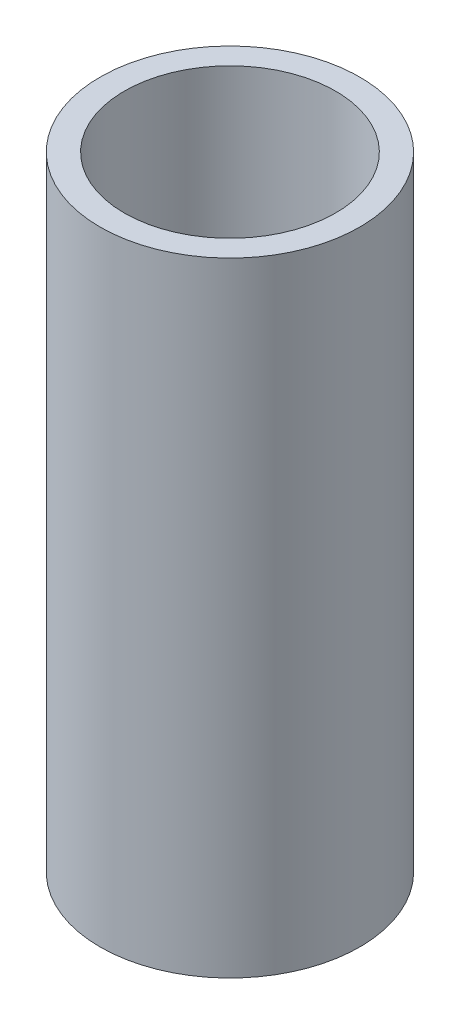
SolidWorks part; units mm, degrees
ref_plane "Front Plane" through (0, 0, 0) normal (0, 0, 1) x (1, 0, 0)
ref_plane "Top Plane" through (0, 0, 0) normal (0, 1, 0) x (1, 0, 0)
ref_plane "Right Plane" through (0, 0, 0) normal (1, 0, 0) x (0, 0, -1)
sketch "Sketch1" plane through (0, 0, 0) normal (0, 1, 0) x (1, 0, 0)
  circle A0 centre (0, 0) radius 3.05
  circle A1 centre (0, 0) radius 3.75
  dimension "D1" = 6.1
  dimension "D2" = 7.5
extrude "Boss-Extrude1" add sketch "Sketch1" along normal blind 18
